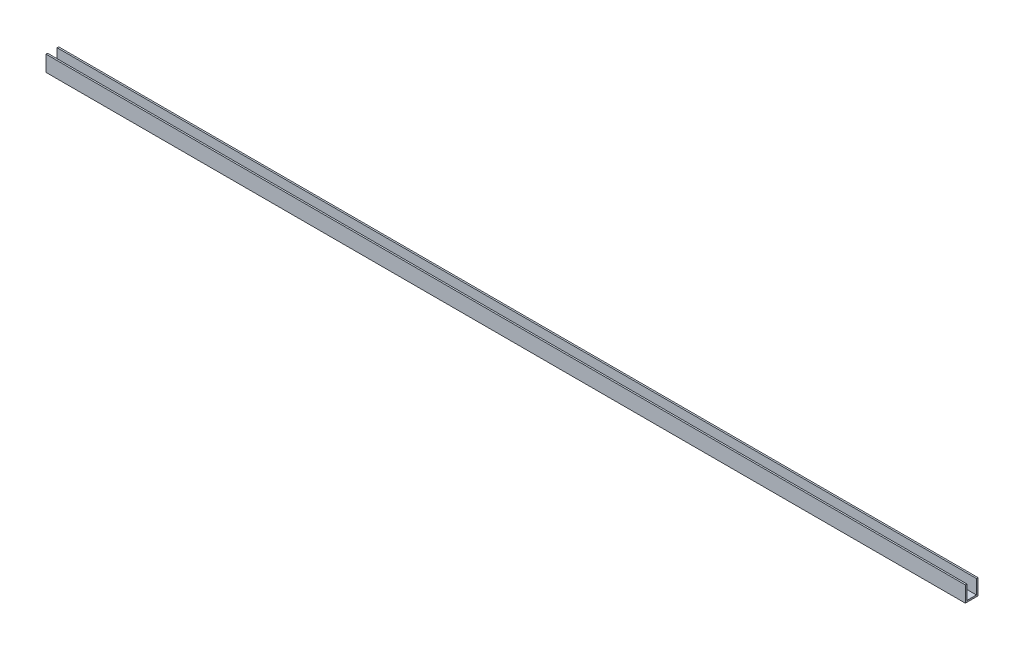
SolidWorks part; units mm, degrees
ref_plane "Front Plane" through (0, 0, 0) normal (0, 0, 1) x (1, 0, 0)
ref_plane "Top Plane" through (0, 0, 0) normal (0, 1, 0) x (1, 0, 0)
ref_plane "Right Plane" through (0, 0, 0) normal (1, 0, 0) x (0, 0, -1)
sketch "Sketch1" plane through (0, 0, 0) normal (1, 0, 0) x (0, 0, -1)
  line L0 (0, 21.5573) -> (0, -20.9315) construction
  line L1 (-36.1687, 0) -> (35.23, 0) construction
  line L2 (-4, 0) -> (4, 0)
  line L3 (4, 0) -> (4, 10)
  line L4 (4, 10) -> (3, 10)
  line L5 (3, 10) -> (3, 1)
  line L6 (3, 1) -> (-3, 1)
  line L7 (-3, 1) -> (-3, 10)
  line L8 (-3, 10) -> (-4, 10)
  line L9 (-4, 10) -> (-4, 0)
  dimension "D1" = 8
  dimension "D2" = 1
  dimension "D3" = 1
  dimension "D4" = 10
extrude "Boss-Extrude1" add sketch "Sketch1" along normal blind 580
ref_plane "Plane1" through (580, 10, 3) normal (-1, 0, 0) x (0, 0, 1)
